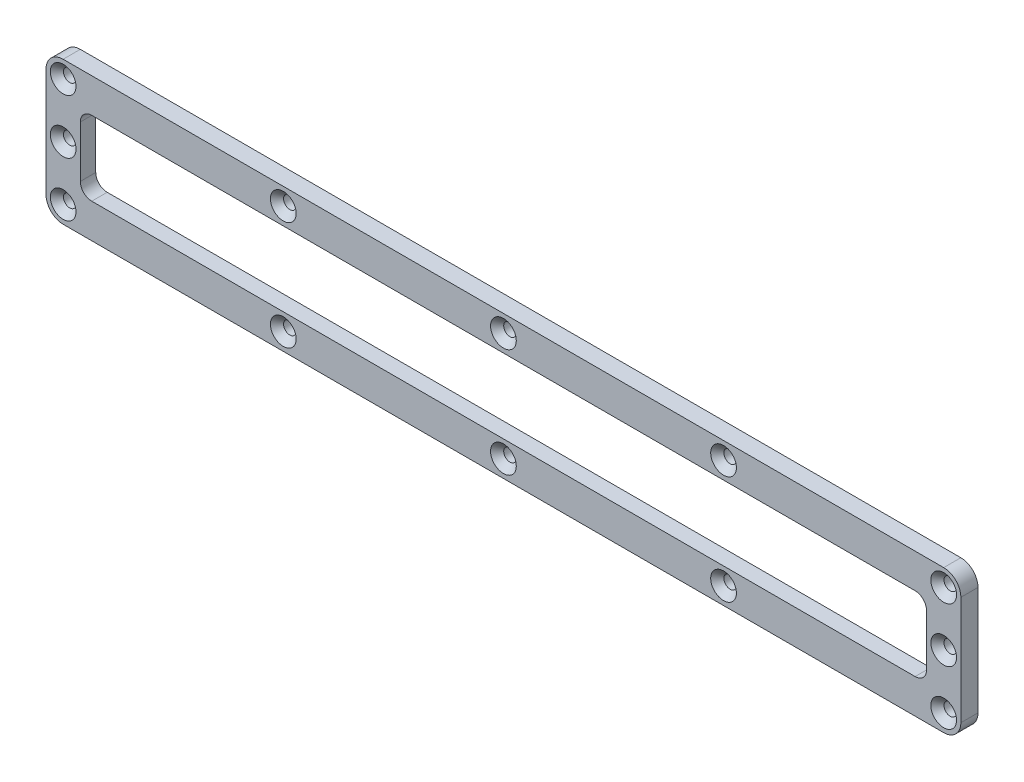
SolidWorks part; units mm, degrees
material "AISI Type 316L stainless steel"
ref_plane "Front Plane" through (0, 0, 0) normal (0, 0, 1) x (1, 0, 0)
ref_plane "Top Plane" through (0, 0, 0) normal (0, 1, 0) x (1, 0, 0)
ref_plane "Right Plane" through (0, 0, 0) normal (1, 0, 0) x (0, 0, -1)
sketch "Sketch1" plane through (0, 0, 0) normal (0, 0, 1) x (1, 0, 0)
  line L1 (-80, 12.5) -> (80, 12.5)
  line L2 (-80, 12.5) -> (-80, -12.5)
  line L3 (-80, -12.5) -> (80, -12.5)
  line L4 (80, 12.5) -> (80, -12.5)
  line L5 (-80, 12.5) -> (80, -12.5) construction
  line L6 (-80, -12.5) -> (80, 12.5) construction
  point P0 (0, 0)
  dimension "D1" = 25
  dimension "D2" = 160
extrude "Boss-Extrude1" add sketch "Sketch1" along normal mid plane 3
sketch "Sketch2" plane through (0, 0, 1.5) normal (0, 0, 1) x (1, 0, 0)
  line L0 (-80, 12.5) -> (-80, -12.5) construction
  line L1 (74, -6.5) -> (-74, -6.5)
  line L2 (74, -6.5) -> (74, 6.5)
  line L3 (74, 6.5) -> (-74, 6.5)
  line L4 (-74, -6.5) -> (-74, 6.5)
  line L5 (74, -6.5) -> (-74, 6.5) construction
  line L6 (74, 6.5) -> (-74, -6.5) construction
  line L7 (80, 12.5) -> (-80, 12.5) construction
  point P0 (0, 0)
  dimension "D1" = 6
  dimension "D2" = 6
extrude "Cut-Extrude1" cut sketch "Sketch2" against normal through all
sketch "Sketch5" plane through (0, 0, 1.5) normal (0, 0, 1) x (1, 0, 0)
  line L0 (74, -6.5) -> (80, -12.5)
  line L1 (-77, 9.5) -> (77, 9.5)
  line L2 (-77, 9.5) -> (-77, -9.5)
  line L3 (-77, -9.5) -> (77, -9.5)
  line L4 (77, 9.5) -> (77, -9.5)
  line L5 (-77, 9.5) -> (77, -9.5) construction
  line L6 (-77, -9.5) -> (77, 9.5) construction
  line L7 (74, -6.5) -> (74, 6.5) construction
  line L8 (-74, -6.5) -> (74, -6.5) construction
  line L9 (0, -9.5) -> (77, -9.5)
  point P11 (0, -9.5)
  point P15 (38.5, -9.5)
  point P19 (77, 0)
fillet "Fillet1" radius 2 4 edges at (74, 6.5, 0) (74, -6.5, 0) (-74, -6.5, 0) (-74, 6.5, 0)
fillet "Fillet2" radius 3 4 edges at (80, -12.5, 0) (-80, -12.5, 0) (80, 12.5, 0) (-80, 12.5, 0)
hole_wizard "CSK for M2 Slotted raised CTSK head screws1" positions "3DSketch1" profile "Sketch6" countersink size "M2" standard "GB" end condition through all
sketch3d "3DSketch1"
  point P0 (0, -9.5, 1.5)
  point P3 (38.5, -9.5, 1.5)
  point P6 (77, -9.5, 1.5)
  point P15 (77, 0, 1.5)
sketch "Sketch6" plane through (0, -9.5, 1.5) normal (1, 0, 0) x (0, -1, 0)
  line L0 (0, 0) -> (0, 3)
  line L1 (0, 3) -> (1.1, 3)
  line L2 (1.1, 3) -> (1.1, 1.15)
  line L3 (1.1, 1.15) -> (2.25, 0)
  line L5 (2.25, 0) -> (0, 0)
  line L6 (-1.1, 1.15) -> (-2.25, 0) construction
  line L11 (0, -6.35) -> (0, 107.95) construction
  dimension "Thru Hole Dia." = 2.2
  dimension "Thru Hole Depth" = 3
  dimension "Near C'Sink Dia." = 4.5
  dimension "Near C'Sink Angle" = 90
mirror "Mirror1" about plane through (0, 0, 0) normal (0, 1, 0) of "CSK for M2 Slotted raised CTSK head screws1" second plane through (0, 0, 0) second plane normal (1, 0, 0)
sketch "Sketch7" plane through (0, 0, -1.5) normal (0, 0, -1) x (-1, 0, 0)
  line L1 (75.5, -8) -> (-75.5, -8)
  line L2 (75.5, -8) -> (75.5, 8)
  line L3 (75.5, 8) -> (-75.5, 8)
  line L4 (-75.5, -8) -> (-75.5, 8)
  line L5 (75.5, -8) -> (-75.5, 8) construction
  line L6 (75.5, 8) -> (-75.5, -8) construction
  line L7 (-80, -9.5) -> (-80, 9.5) construction
  line L8 (-77, 12.5) -> (77, 12.5) construction
  point P9 (0, 0)
  dimension "D1" = 4.5
  dimension "D2" = 4.5
extrude "Cut-Extrude2" cut sketch "Sketch7" against normal blind 0.3
fillet "Fillet4" radius 1 4 edges at (-75.5, 8, -1.35) (-75.5, -8, -1.35) (75.5, -8, -1.35) (75.5, 8, -1.35)
